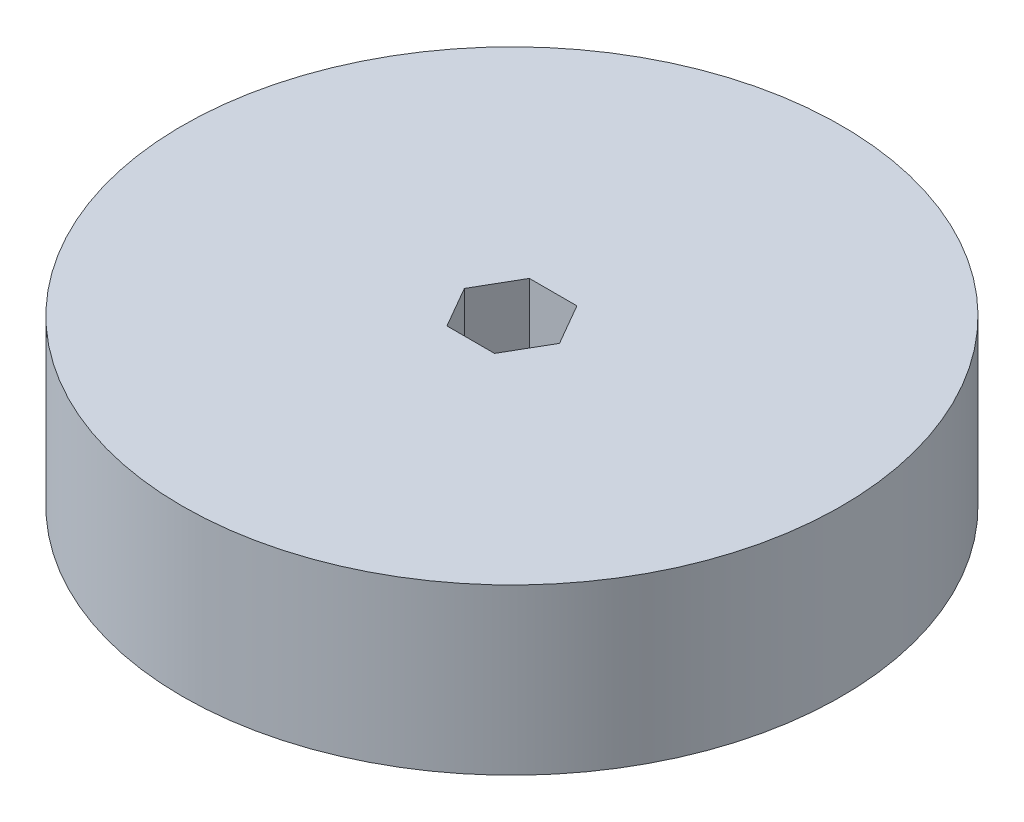
SolidWorks part; units mm, degrees
ref_plane "Front Plane" through (0, 0, 0) normal (0, 0, 1) x (1, 0, 0)
ref_plane "Top Plane" through (0, 0, 0) normal (0, 1, 0) x (1, 0, 0)
ref_plane "Right Plane" through (0, 0, 0) normal (1, 0, 0) x (0, 0, -1)
sketch "Sketch1" plane through (0, 0, 0) normal (0, 1, 0) x (1, 0, 0)
  circle A0 centre (0, 0) radius 50.8
  dimension "D1" = 101.6
extrude "Boss-Extrude1" add sketch "Sketch1" along normal blind 25.4 contours A0
sketch "Sketch2" plane through (0, 25.4, 0) normal (0, 1, 0) x (1, 0, 0)
  line L1 (3.6662, 6.35) -> (-3.6662, 6.35)
  line L2 (-3.6662, 6.35) -> (-7.3323, 0)
  line L3 (-7.3323, 0) -> (-3.6662, -6.35)
  line L4 (-3.6662, -6.35) -> (3.6662, -6.35)
  line L5 (3.6662, -6.35) -> (7.3323, 0)
  line L6 (7.3323, 0) -> (3.6662, 6.35)
  circle A0 centre (0, 0) radius 6.35 construction
  dimension "D1" = 12.7
extrude "Cut-Extrude1" cut sketch "Sketch2" against normal through all
